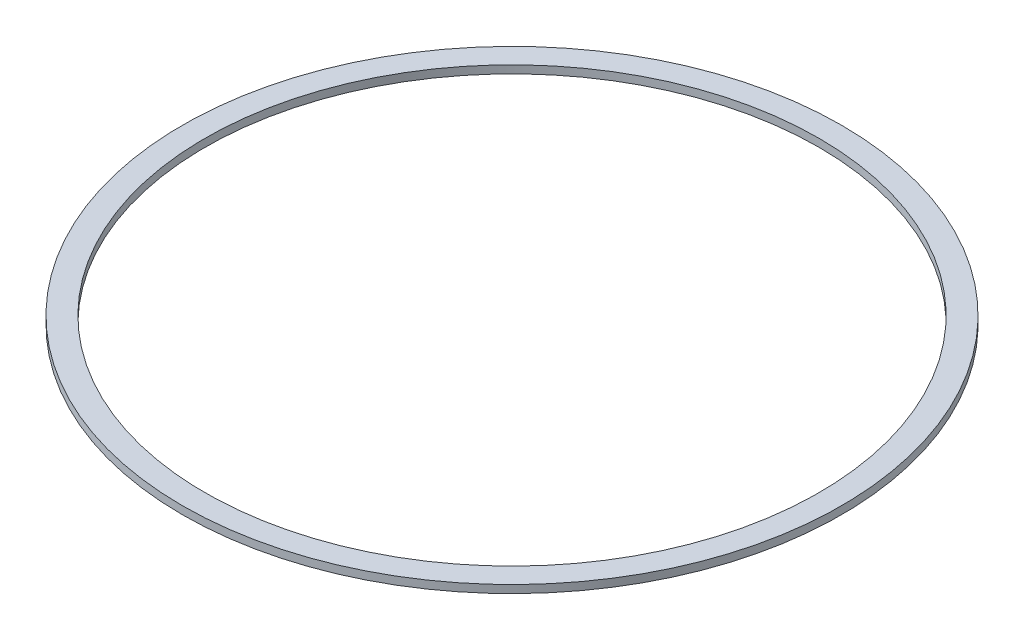
SolidWorks part; units mm, degrees
material "Hexcel AS4C (3000 Filaments)"
ref_plane "Front Plane" through (0, 0, 0) normal (0, 0, 1) x (1, 0, 0)
ref_plane "Top Plane" through (0, 0, 0) normal (0, 1, 0) x (1, 0, 0)
ref_plane "Right Plane" through (0, 0, 0) normal (1, 0, 0) x (0, 0, -1)
sketch "Sketch1" plane through (0, 0, 0) normal (0, 0, 1) x (1, 0, 0)
  line L0 (-102, 3.175) -> (-102, 5.785) construction
  line L1 (-109.5, 3.175) -> (-109.5, 5.785) construction
  line L2 (-102, 3.175) -> (-102, 5.785)
  line L3 (-109.5, 3.175) -> (-109.5, 5.785)
  line L4 (-109.5, 5.785) -> (-102, 5.785)
  line L5 (-102, 3.175) -> (-109.5, 3.175)
  line L6 (0, -200069.0475) -> (0, 200086.9028) construction
  line L7 (0, -200069.0475) -> (0, 200086.9028) construction
revolve "Revolve1" add sketch "Sketch1" angle 360 about L7
